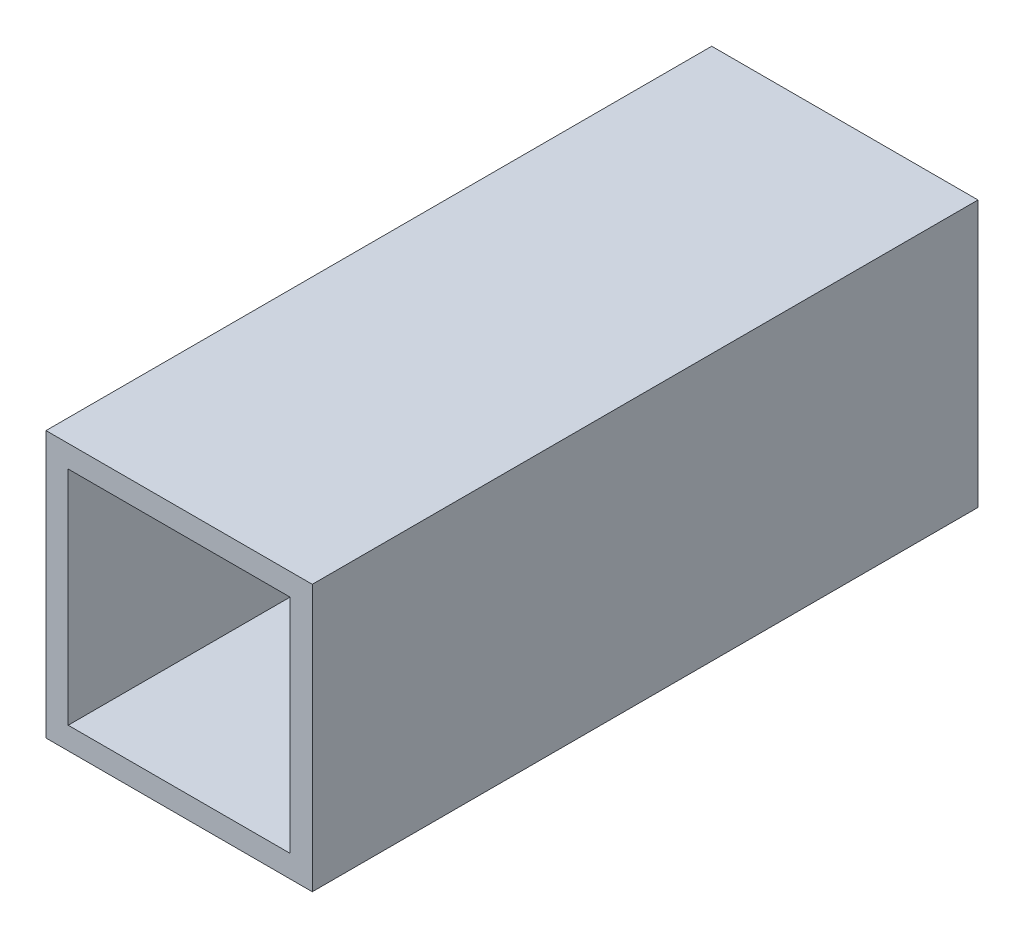
SolidWorks part; units mm, degrees
ref_plane "前视基准面" through (0, 0, 0) normal (0, 0, 1) x (1, 0, 0)
ref_plane "上视基准面" through (0, 0, 0) normal (0, 1, 0) x (1, 0, 0)
ref_plane "右视基准面" through (0, 0, 0) normal (1, 0, 0) x (0, 0, -1)
sketch "草图1" plane through (0, 0, 0) normal (0, 0, 1) x (1, 0, 0)
  line L0 (-12, 12) -> (12, 12)
  line L1 (-10, 10) -> (10, 10)
  line L2 (-10, 10) -> (-10, -10)
  line L3 (-10, -10) -> (10, -10)
  line L4 (10, 10) -> (10, -10)
  line L5 (-10, 10) -> (10, -10) construction
  line L6 (-10, -10) -> (10, 10) construction
  line L7 (12, 12) -> (12, -12)
  line L8 (-12, -12) -> (12, -12)
  line L9 (-12, 12) -> (-12, -12)
  point P0 (0, 0)
  dimension "D1" = 20
  dimension "D2" = 20
  dimension "D3" = 2
extrude "凸台-拉伸1" add sketch "草图1" along normal blind 60
